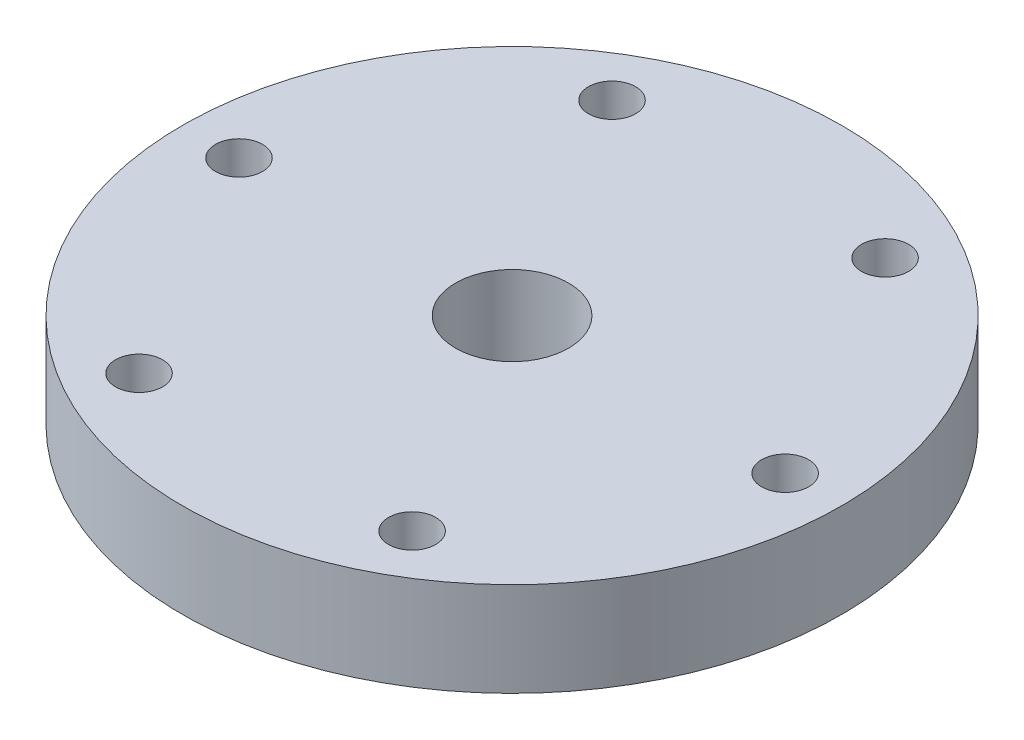
SolidWorks part; units mm, degrees
ref_plane "Alzado" through (0, 0, 0) normal (0, 0, 1) x (1, 0, 0)
ref_plane "Planta" through (0, 0, 0) normal (0, 1, 0) x (1, 0, 0)
ref_plane "Vista lateral" through (0, 0, 0) normal (1, 0, 0) x (0, 0, -1)
sketch "Croquis1" plane through (0, 0, 0) normal (0, 0, 1) x (1, 0, 0)
  line L0 (2, 0) -> (2, 15)
  line L1 (2, 15) -> (35, 15)
  line L2 (35, 15) -> (35, 5)
  line L3 (35, 5) -> (15, 5)
  line L4 (15, 5) -> (15, 0)
  line L5 (15, 0) -> (2, 0)
  line L6 (0, 0) -> (0, 5.5051) construction
  dimension "D1" = 4
  dimension "D3" = 10
  dimension "D4" = 15
  dimension "D5" = 0
  dimension "D2" = 30
  dimension "D6" = 70
revolve "Revolución1" add sketch "Croquis1" angle 360 about L6
fillet "Redondeo1" radius 2 1 edges at (0, 5, -15)
sketch "Croquis2" plane through (0, 15, 0) normal (0, 1, 0) x (1, 0, 0)
  circle A0 centre (0, 0) radius 29 construction
  circle A1 centre (29, 0) radius 1.5
  point P3 (29, 0)
  dimension "D1" = 58
  dimension "D2" = 3
hole_wizard "Taladro roscado M61" positions "Croquis2" profile "Croquis3" tap size "M6" standard "DIN" end condition through all
cosmetic thread "Rosca cosmética1" parameters "D2"=6
sketch "Croquis3" plane through (29, 15, 0) normal (1, 0, 0) x (0, 0, 1)
  line L0 (0, 0) -> (0, 15)
  line L1 (0, 15) -> (2.5, 15)
  line L2 (2.5, 15) -> (2.5, 0)
  line L5 (2.5, 0) -> (0, 0)
  line L11 (0, -6.35) -> (0, 107.95) construction
  dimension "Diámetro de perforador para roscar hasta el siguiente" = 5
  dimension "Profundidad de perforador para roscar hasta el siguiente" = 15
thread "Rosca1" [suppressed] pitch 1.5 start angle 0, offset 0, length 20, pitch 1.5, diameter 14
ref_plane "Plano1" through (-7, 16.3125, 0) normal (0, 0, 1) x (-1, 0, 0)
sketch "Perfil de rosca1" plane through (-7, 16.3125, 0) normal (0, 0, 1) x (-1, 0, 0)
  line L0 (0, 0) -> (0, 1.5) construction
  line L11 (0, 0) -> (0, 1.3125)
  line L12 (0, 1.3125) -> (-0.8119, 0.8437)
  line L13 (-0.8119, 0.8437) -> (-0.8119, 0.4687)
  line L15 (-0.8119, 0.4687) -> (0, 0)
  line L17 (-0.8119, 0.6562) -> (0, 0.6562) construction
  point P2 (0, 0)
  dimension "Pitch" = 1.5
  dimension "Profile_Angle" = 60
  dimension "Profile_Land" = 0.375
  dimension "Profile_Height" = 0.8119
sketch "Croquis7" plane through (0, 15, 0) normal (0, 1, 0) x (1, 0, 0)
  circle A0 centre (0, 0) radius 12.054
  point P0 (0, 0)
hole_wizard "Taladro roscado M141" positions "Croquis7" profile "Croquis10" tap size "M14" standard "DIN" end condition through all
cosmetic thread "Rosca cosmética35" parameters "D2"=14
sketch "Croquis10" plane through (0, 15, 0) normal (1, 0, 0) x (0, 0, 1)
  line L0 (0, 0) -> (0, 15)
  line L1 (0, 15) -> (6, 15)
  line L2 (6, 15) -> (6, 0)
  line L5 (6, 0) -> (0, 0)
  line L11 (0, -6.35) -> (0, 107.95) construction
  dimension "Diámetro de perforador para roscar hasta el siguiente" = 12
  dimension "Profundidad de perforador para roscar hasta el siguiente" = 15
pattern_circular "MatrizC1" count 6 over 360 about axis through (0, 0, 0) along (0, 1, 0) of "Taladro roscado M61"
cosmetic thread "Rosca cosmética2"
cosmetic thread "Rosca cosmética3"
cosmetic thread "Rosca cosmética4"
cosmetic thread "Rosca cosmética5"
cosmetic thread "Rosca cosmética6"
cosmetic thread "Rosca cosmética24"
cosmetic thread "Rosca cosmética25"
cosmetic thread "Rosca cosmética26"
cosmetic thread "Rosca cosmética33"
cosmetic thread "Rosca cosmética34"
sketch "Croquis6" plane through (0, 0, 0) normal (0, 0, 1) x (1, 0, 0)
  line L0 (-35, 15) -> (-35, 5)
  line L1 (0, 0) -> (13.9755, 0)
  line L2 (0, 0) -> (0, -5.781)
  line L3 (0, -5.781) -> (13.9755, -5.781)
  line L4 (13.9755, 0) -> (13.9755, -5.781)
  line L5 (35, 5) -> (35, 15)
  line L6 (35, 5) -> (35, 15)
  line L7 (-35, 15) -> (-35, 5)
  line L8 (-35, 15) -> (35, 15)
  line L10 (0, 15) -> (15, 15)
  line L11 (0, 15) -> (0, 20.8383)
  line L12 (0, 20.8383) -> (15, 20.8383)
  line L13 (15, 15) -> (15, 20.8383)
revolve "Cortar-Revolución1" [suppressed] cut sketch "Croquis6" angle 360 about L2
equation "\"DIRodamiento\"=4"
equation "\"L1\"=5"
equation "\"L2\"=15"
equation "\"D1@Croquis1\"=\"DIRodamiento\""
equation "\"D4@Croquis1\"=\"L2\""
equation "\"D12Rodamiento\"=30"
equation "\"D2@Croquis1\"=\"D12Rodamiento\""
